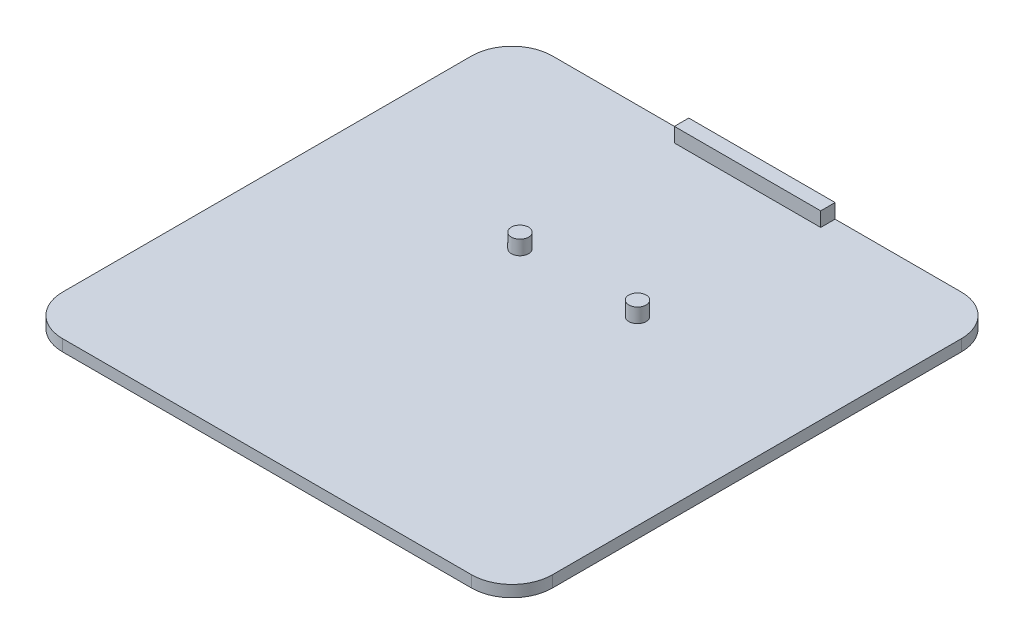
SolidWorks part; units mm, degrees
ref_plane "Front Plane" through (0, 0, 0) normal (0, 0, 1) x (1, 0, 0)
ref_plane "Top Plane" through (0, 0, 0) normal (0, 1, 0) x (1, 0, 0)
ref_plane "Right Plane" through (0, 0, 0) normal (1, 0, 0) x (0, 0, -1)
sketch "Sketch1" plane through (0, 0, 0) normal (0, 1, 0) x (1, 0, 0)
  line L0 (-35.8925, -26.5223) -> (35.1075, -26.5223)
  line L1 (42.1075, -19.5223) -> (42.1075, 51.4777)
  line L2 (35.1075, 58.4777) -> (-35.8925, 58.4777)
  line L3 (-42.8925, 51.4777) -> (-42.8925, -19.5223)
  arc A0 (-42.8925, 51.4777) -> (-35.8925, 58.4777) centre (-35.8925, 51.4777) cw
  arc A1 (42.1075, 51.4777) -> (35.1075, 58.4777) centre (35.1075, 51.4777) ccw
  arc A2 (35.1075, -26.5223) -> (42.1075, -19.5223) centre (35.1075, -19.5223) ccw
  arc A3 (-42.8925, -19.5223) -> (-35.8925, -26.5223) centre (-35.8925, -19.5223) ccw
  dimension "D1" = 7
  dimension "D2" = 7
  dimension "D3" = 7
  dimension "D4" = 7
extrude "Boss-Extrude1" add sketch "Sketch1" along normal blind 2
sketch "Sketch2" plane through (0, 2, 0) normal (0, 1, 0) x (1, 0, 0)
  line L1 (35.1075, 58.4777) -> (-35.8925, 58.4777) construction
  line L8 (-12.2116, 58.4777) -> (-12.2116, 55.9777)
  line L9 (-12.2116, 55.9777) -> (13.1884, 55.9777)
  line L10 (13.1884, 55.9777) -> (13.1884, 58.4777)
  line L11 (13.1884, 58.4777) -> (-12.2116, 58.4777)
  circle A0 centre (-9.7116, 26.679) radius 1.5
  circle A1 centre (10.6884, 26.679) radius 1.5
extrude "Boss-Extrude2" add sketch "Sketch2" along normal blind 2.5
